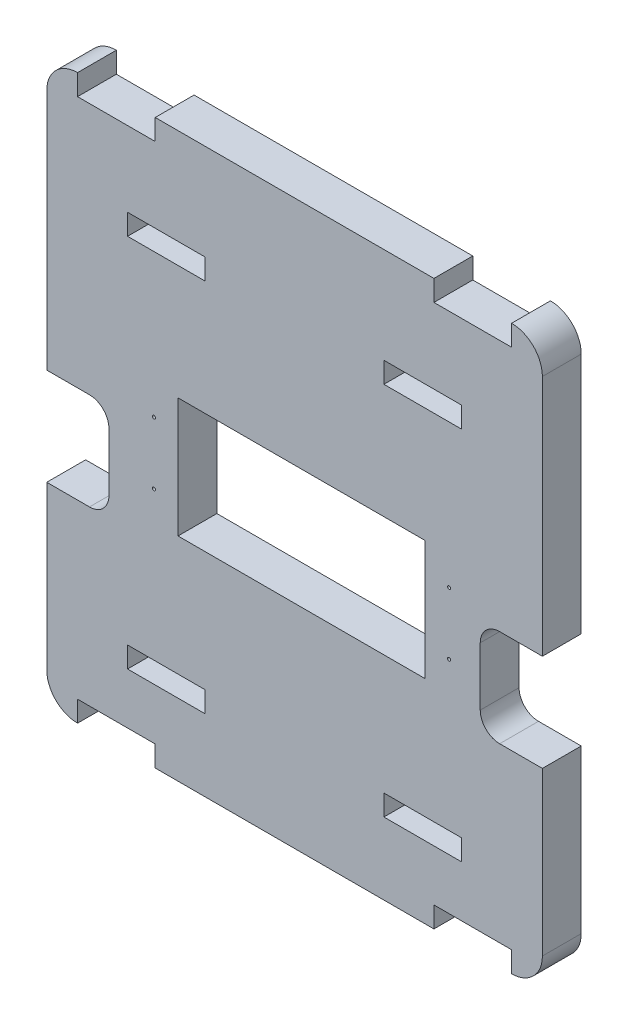
SolidWorks part; units mm, degrees
ref_plane "Front Plane" through (0, 0, 0) normal (0, 0, 1) x (1, 0, 0)
ref_plane "Top Plane" through (0, 0, 0) normal (0, 1, 0) x (1, 0, 0)
ref_plane "Right Plane" through (0, 0, 0) normal (1, 0, 0) x (0, 0, -1)
sketch "Sketch1" plane through (0, 0, 0) normal (0, 0, 1) x (1, 0, 0)
  line L0 (6728.6354, 3585.1497) -> (6728.6354, 3545.5403)
  line L1 (6728.6354, 3529.6653) -> (6728.6354, 3503.0969)
  line L2 (6746.3646, 3590.1789) -> (6791.9322, 3590.1789)
  line L3 (6733.6646, 3586.7753) -> (6746.3646, 3586.7753)
  line L4 (6791.9322, 3586.7753) -> (6804.6322, 3586.7753)
  line L5 (6809.6614, 3585.1497) -> (6809.6614, 3545.5403)
  line L6 (6809.6614, 3529.6653) -> (6809.6614, 3503.0969)
  line L7 (6746.3646, 3498.0677) -> (6791.9322, 3498.0677)
  line L8 (6733.6646, 3501.4713) -> (6746.3646, 3501.4713)
  line L9 (6791.9322, 3501.4713) -> (6804.6322, 3501.4713)
  line L10 (6809.6614, 3545.5403) -> (6802.6764, 3545.5403)
  line L11 (6809.6614, 3529.6653) -> (6802.6764, 3529.6653)
  line L12 (6799.5014, 3542.3653) -> (6799.5014, 3532.8403)
  line L13 (6728.6354, 3545.5403) -> (6735.6204, 3545.5403)
  line L14 (6728.6354, 3529.6653) -> (6735.6204, 3529.6653)
  line L15 (6738.7954, 3542.3653) -> (6738.7954, 3532.8403)
  line L16 (6741.8434, 3513.2315) -> (6741.8434, 3509.8279)
  line L17 (6754.5434, 3513.2315) -> (6754.5434, 3509.8279)
  line L18 (6796.4534, 3513.2315) -> (6796.4534, 3509.8279)
  line L19 (6783.7534, 3513.2315) -> (6783.7534, 3509.8279)
  line L20 (6796.4534, 3571.0927) -> (6796.4534, 3574.4963)
  line L21 (6783.7534, 3571.0927) -> (6783.7534, 3574.4963)
  line L22 (6741.8434, 3571.0927) -> (6741.8434, 3574.4963)
  line L23 (6754.5434, 3571.0927) -> (6754.5434, 3574.4963)
  line L24 (6741.8434, 3574.4963) -> (6754.5434, 3574.4963)
  line L25 (6741.8434, 3571.0927) -> (6754.5434, 3571.0927)
  line L26 (6783.7534, 3574.4963) -> (6796.4534, 3574.4963)
  line L27 (6783.7534, 3571.0927) -> (6796.4534, 3571.0927)
  line L28 (6796.4534, 3509.8279) -> (6783.7534, 3509.8279)
  line L29 (6796.4534, 3513.2315) -> (6783.7534, 3513.2315)
  line L30 (6754.5434, 3509.8279) -> (6741.8434, 3509.8279)
  line L31 (6754.5434, 3513.2315) -> (6741.8434, 3513.2315)
  line L32 (6733.6646, 3586.7753) -> (6733.6646, 3590.1789)
  line L33 (6746.3646, 3586.7753) -> (6746.3646, 3590.1789)
  line L34 (6804.6322, 3586.7753) -> (6804.6322, 3590.1789)
  line L35 (6791.9322, 3586.7753) -> (6791.9322, 3590.1789)
  line L36 (6733.6646, 3501.4713) -> (6733.6646, 3498.0677)
  line L37 (6746.3646, 3501.4713) -> (6746.3646, 3498.0677)
  line L38 (6804.6322, 3501.4713) -> (6804.6322, 3498.0677)
  line L39 (6791.9322, 3501.4713) -> (6791.9322, 3498.0677)
  line L40 (6750.0933, 3552.3471) -> (6750.0933, 3532.7891)
  line L41 (6750.0933, 3532.7891) -> (6790.4793, 3532.7891)
  line L42 (6790.4793, 3532.7891) -> (6790.4793, 3552.3471)
  line L43 (6790.4793, 3552.3471) -> (6750.0933, 3552.3471)
  arc A0 (6733.6646, 3590.1789) -> (6728.6354, 3585.1497) centre (6733.6646, 3585.1497) ccw
  arc A1 (6809.6614, 3585.1497) -> (6804.6322, 3590.1789) centre (6804.6322, 3585.1497) ccw
  arc A2 (6804.6322, 3498.0677) -> (6809.6614, 3503.0969) centre (6804.6322, 3503.0969) ccw
  arc A3 (6728.6354, 3503.0969) -> (6733.6646, 3498.0677) centre (6733.6646, 3503.0969) ccw
  arc A4 (6799.5014, 3532.8403) -> (6802.6764, 3529.6653) centre (6802.6764, 3532.8403) ccw
  arc A5 (6802.6764, 3545.5403) -> (6799.5014, 3542.3653) centre (6802.6764, 3542.3653) ccw
  arc A6 (6735.6204, 3529.6653) -> (6738.7954, 3532.8403) centre (6735.6204, 3532.8403) ccw
  arc A7 (6738.7954, 3542.3653) -> (6735.6204, 3545.5403) centre (6735.6204, 3542.3653) ccw
  circle A8 centre (6794.4163, 3547.6481) radius 0.254
  circle A9 centre (6794.4163, 3537.4881) radius 0.254
  circle A10 centre (6746.1563, 3547.6481) radius 0.254
  circle A11 centre (6746.1563, 3537.4881) radius 0.254
extrude "Boss-Extrude1" add sketch "Sketch1" along normal blind 6.35
